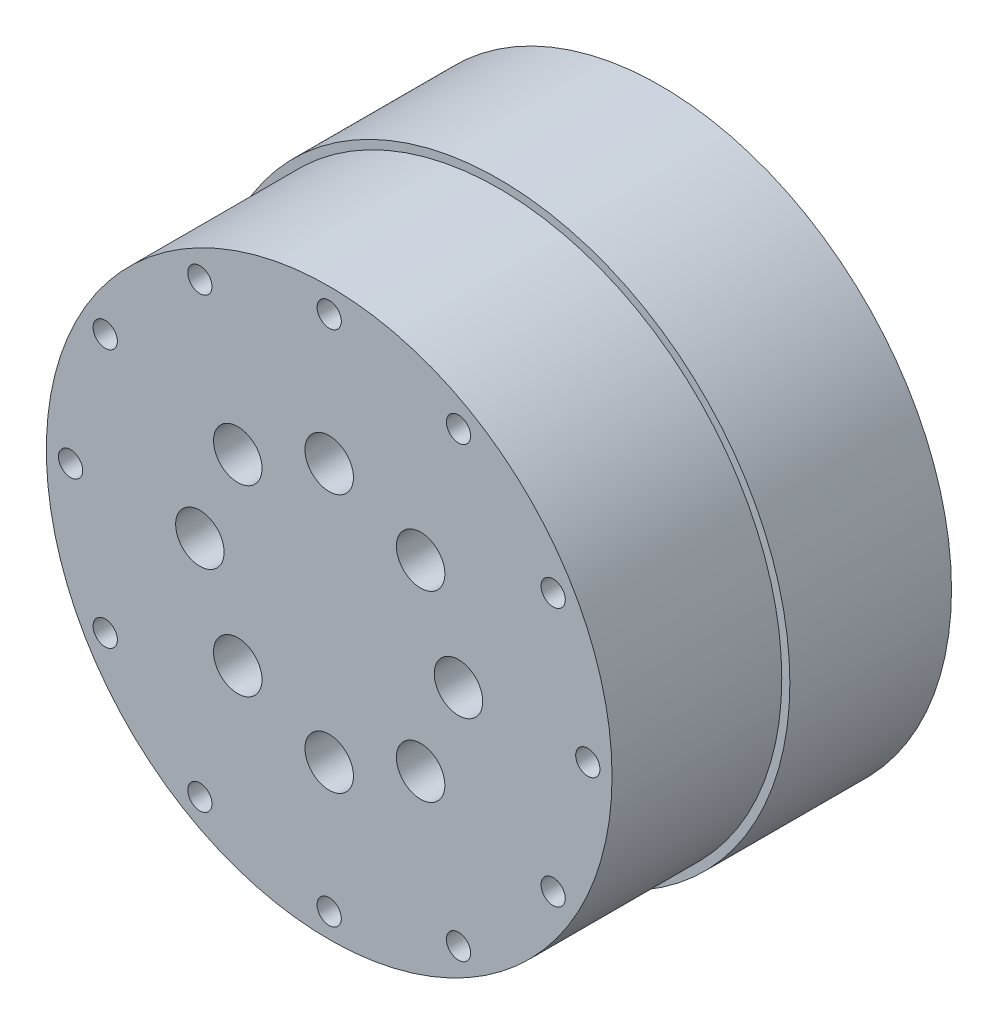
SolidWorks part; units mm, degrees
ref_plane "前视基准面" through (0, 0, 0) normal (0, 0, 1) x (1, 0, 0)
ref_plane "上视基准面" through (0, 0, 0) normal (0, 1, 0) x (1, 0, 0)
ref_plane "右视基准面" through (0, 0, 0) normal (1, 0, 0) x (0, 0, -1)
sketch "草图1" plane through (0, 0, 0) normal (0, 0, 1) x (1, 0, 0)
  circle A0 centre (0, 0) radius 36
  circle A1 centre (32, 0) radius 1.5
  circle A2 centre (27.7128, -16) radius 1.5
  circle A3 centre (16, -27.7128) radius 1.5
  circle A4 centre (0, -32) radius 1.5
  circle A5 centre (-16, -27.7128) radius 1.5
  circle A6 centre (-27.7128, -16) radius 1.5
  circle A7 centre (-32, 0) radius 1.5
  circle A8 centre (-27.7128, 16) radius 1.5
  circle A9 centre (-16, 27.7128) radius 1.5
  circle A10 centre (0, 32) radius 1.5
  circle A11 centre (16, 27.7128) radius 1.5
  circle A12 centre (27.7128, 16) radius 1.5
  dimension "D1" = 72
  dimension "D2" = 3
  dimension "D3" = 32
  dimension "D4" = 12
extrude "凸台-拉伸1" add sketch "草图1" along normal blind 41
sketch "草图2" plane through (0, 0, 41) normal (0, 0, 1) x (1, 0, 0)
  circle A0 centre (16, 0) radius 3
  circle A1 centre (11.3137, -11.3137) radius 3
  circle A2 centre (0, -16) radius 3
  circle A3 centre (-11.3137, -11.3137) radius 3
  circle A4 centre (-16, 0) radius 3
  circle A5 centre (-11.3137, 11.3137) radius 3
  circle A6 centre (0, 16) radius 3
  circle A7 centre (11.3137, 11.3137) radius 3
  point P2 (0, 0)
  dimension "D1" = 6
  dimension "D2" = 16
  dimension "D3" = 8
extrude "切除-拉伸1" cut sketch "草图2" against normal blind 12
sketch "草图3" plane through (0, 0, 0) normal (0, 0, -1) x (-1, 0, 0)
  circle A0 centre (0, 0) radius 4
  dimension "D1" = 8
extrude "切除-拉伸2" cut sketch "草图3" against normal blind 12
sketch "草图4" plane through (0, 0, 0) normal (0, 0, -1) x (-1, 0, 0)
  circle A0 centre (7, 0) radius 1.25
  circle A1 centre (0, -7) radius 1.25
  circle A2 centre (-7, 0) radius 1.25
  circle A3 centre (0, 7) radius 1.25
  dimension "D1" = 2.5
  dimension "D3" = 7
  dimension "D2" = 4
extrude "切除-拉伸3" cut sketch "草图4" against normal blind 12
sketch "草图5" plane through (0, 0, 41) normal (0, 0, 1) x (1, 0, 0)
  circle A1 centre (0, 0) radius 35
  circle A2 centre (0, 0) radius 36
  circle A3 centre (0, 0) radius 36
  dimension "D2" = 70
  dimension "D1" = 0
extrude "切除-拉伸4" cut sketch "草图5" against normal blind 21
